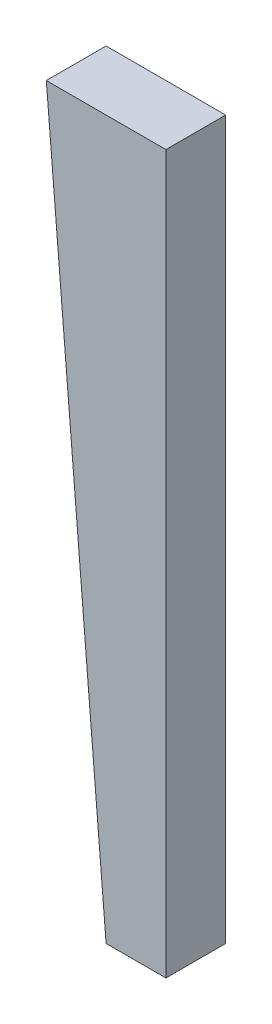
SolidWorks part; units mm, degrees
ref_plane "Plan de face" through (0, 0, 0) normal (0, 0, 1) x (1, 0, 0)
ref_plane "Plan de dessus" through (0, 0, 0) normal (0, 1, 0) x (1, 0, 0)
ref_plane "Plan de droite" through (0, 0, 0) normal (1, 0, 0) x (0, 0, -1)
sketch "Esquisse1" plane through (0, 0, 0) normal (0, 0, 1) x (1, 0, 0)
  line L0 (-1, 6) -> (0, -6)
  line L1 (-1, 6) -> (1, 6) construction
  line L2 (-1, 6) -> (-1, -6) construction
  line L3 (-1, -6) -> (1, -6) construction
  line L4 (1, 6) -> (1, -6) construction
  line L5 (0, -6) -> (1, -6)
  line L6 (1, -6) -> (1, 6)
  line L7 (1, 6) -> (-1, 6)
  point P4 (0, -6)
  dimension "D1" = 6
  dimension "D2" = 6
  dimension "D3" = 2
  dimension "D4" = 1
  dimension "D5" = 1
extrude "Boss.-Extru.1" add sketch "Esquisse1" along normal blind 1
